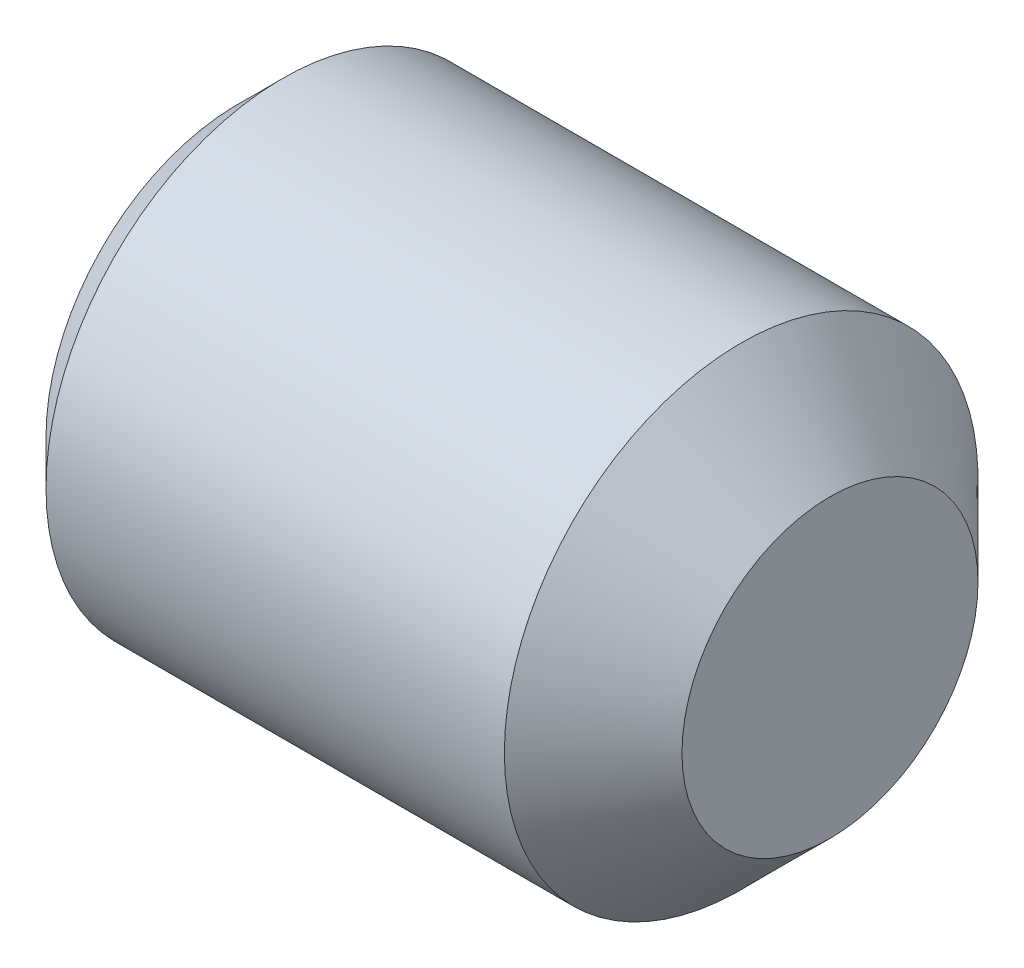
SolidWorks part; units mm, degrees
ref_plane "Front Plane" through (0, 0, 0) normal (0, 0, 1) x (1, 0, 0)
ref_plane "Top Plane" through (0, 0, 0) normal (0, 1, 0) x (1, 0, 0)
ref_plane "Right Plane" through (0, 0, 0) normal (1, 0, 0) x (0, 0, -1)
sketch "Sketch1" plane through (0, 0, 0) normal (0, 0, 1) x (1, 0, 0)
  line L0 (5, 1.25) -> (5, 0)
  line L1 (0, 1.621) -> (0.379, 2)
  line L2 (0, 0) -> (5, 0) construction
  line L3 (0, 0) -> (0, 1.621)
  line L4 (0.379, 2) -> (4.25, 2)
  line L5 (0, 0) -> (5, 0)
  line L6 (4.25, 2) -> (5, 1.25)
  dimension "FIX_1" = 5
  dimension "MSM_82" = 4
  dimension "MSM_81" = 3.242
  dimension "MSM_83" = 2.5
  dimension "FIX_2" = 45
revolve "Revolve1" add sketch "Sketch1" angle 360 about L2
cosmetic thread "Thread2" parameters "ATD_1"=3.242
sketch "Sketch2" plane through (0, 0, 0) normal (0, 0, 1) x (1, 0, 0)
  line L0 (2.5, 1) -> (0, 1)
  line L1 (3.0774, 0) -> (2.5, 1)
  line L2 (0, 0) -> (3.0774, 0)
  line L3 (0, 0) -> (3.0774, 0) construction
  line L4 (0, 1) -> (0, 0)
  dimension "MSM_84" = 2.5
  dimension "MSM_85" = 2
  dimension "FIX_4" = 60
revolve "Cut-Revolve1" cut sketch "Sketch2" angle 360 about L3
sketch "Sketch3" plane through (0, 0, 0) normal (-1, 0, 0) x (0, 0, 1)
  line L1 (0, 1.1547) -> (-1, 0.5774)
  line L2 (-1, 0.5774) -> (-1, -0.5774)
  line L3 (-1, -0.5774) -> (0, -1.1547)
  line L4 (0, -1.1547) -> (1, -0.5774)
  line L5 (1, -0.5774) -> (1, 0.5774)
  line L6 (1, 0.5774) -> (0, 1.1547)
  circle A0 centre (0, 0) radius 1 construction
  dimension "MSM_85" = 2
extrude "Cut-Extrude1" cut sketch "Sketch3" against normal blind 2.5
